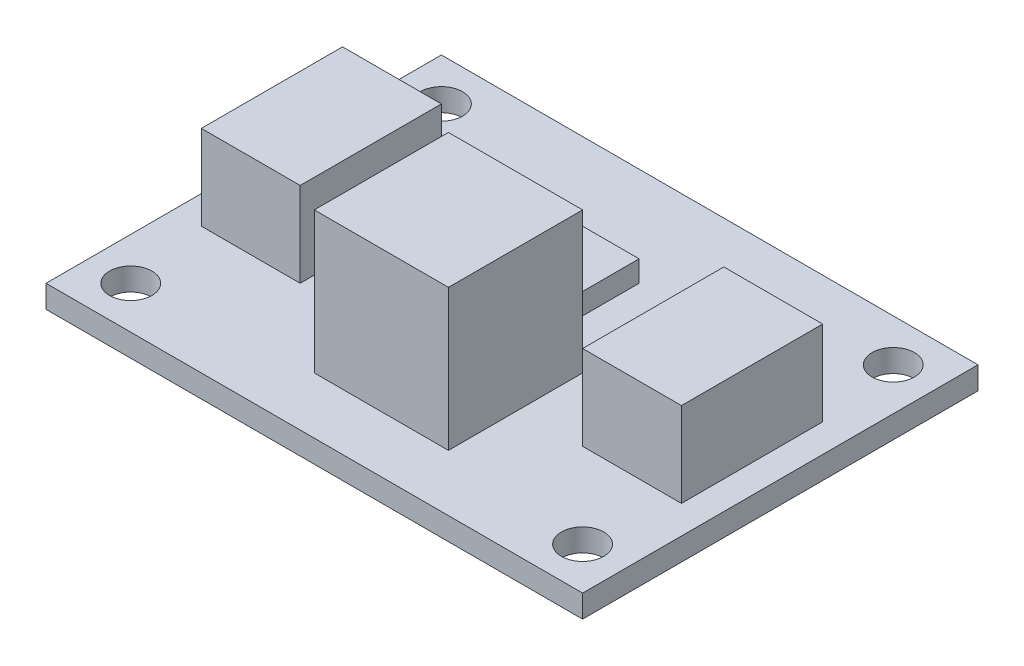
SolidWorks part; units mm, degrees
ref_plane "Front Plane" through (0, 0, 0) normal (0, 0, 1) x (1, 0, 0)
ref_plane "Top Plane" through (0, 0, 0) normal (0, 1, 0) x (1, 0, 0)
ref_plane "Right Plane" through (0, 0, 0) normal (1, 0, 0) x (0, 0, -1)
other "Configuration Table"
sketch "Sketch1" plane through (0, 0, 0) normal (0, 1, 0) x (1, 0, 0)
  line L1 (0, 0) -> (38, 0)
  line L2 (0, 0) -> (0, 28)
  line L3 (0, 28) -> (38, 28)
  line L4 (38, 0) -> (38, 28)
extrude "PCB" add sketch "Sketch1" along normal blind 1.6
sketch "Sketch2" plane through (0, 0, 0) normal (0, 1, 0) x (1, 0, 0)
  circle A0 centre (3, 3) radius 1.5
extrude "Mount_hole_1" cut sketch "Sketch2" against normal through all and the other way through all
sketch "Sketch3" plane through (0, 0, 0) normal (0, 1, 0) x (1, 0, 0)
  circle A0 centre (35, 3) radius 1.5
extrude "Mount_hole_2" cut sketch "Sketch3" against normal through all and the other way through all
sketch "Sketch4" plane through (0, 0, 0) normal (0, 1, 0) x (1, 0, 0)
  circle A0 centre (3, 25) radius 1.5
extrude "Mount_hole_3" cut sketch "Sketch4" against normal through all and the other way through all
sketch "Sketch5" plane through (0, 0, 0) normal (0, 1, 0) x (1, 0, 0)
  circle A0 centre (35, 25) radius 1.5
extrude "Mount_hole_4" cut sketch "Sketch5" against normal through all and the other way through all
sketch "Sketch6" plane through (0, 0, 0) normal (0, 1, 0) x (1, 0, 0)
  line L1 (2, 9) -> (9, 9)
  line L2 (2, 9) -> (2, 19)
  line L3 (2, 19) -> (9, 19)
  line L4 (9, 9) -> (9, 19)
extrude "Sensor_connector" add sketch "Sketch6" along normal blind 6 from offset 1.6
sketch "Sketch7" plane through (0, 0, 0) normal (0, 1, 0) x (1, 0, 0)
  line L1 (29, 9) -> (36, 9)
  line L2 (29, 9) -> (29, 19)
  line L3 (29, 19) -> (36, 19)
  line L4 (36, 9) -> (36, 19)
extrude "Signal_connector" add sketch "Sketch7" along normal blind 6 from offset 1.6
sketch "Sketch8" plane through (0, 0, 0) normal (0, 1, 0) x (1, 0, 0)
  line L1 (15, 4) -> (24.5, 4)
  line L2 (15, 4) -> (15, 13.5)
  line L3 (15, 13.5) -> (24.5, 13.5)
  line L4 (24.5, 4) -> (24.5, 13.5)
extrude "Threshold_pot" add sketch "Sketch8" along normal blind 10 from offset 1.6
sketch "Sketch9" plane through (0, 0, 0) normal (0, 1, 0) x (1, 0, 0)
  line L1 (16, 17) -> (21, 17)
  line L2 (16, 17) -> (16, 21)
  line L3 (16, 21) -> (21, 21)
  line L4 (21, 17) -> (21, 21)
extrude "Comparator" add sketch "Sketch9" along normal blind 1.5 from offset 1.6
